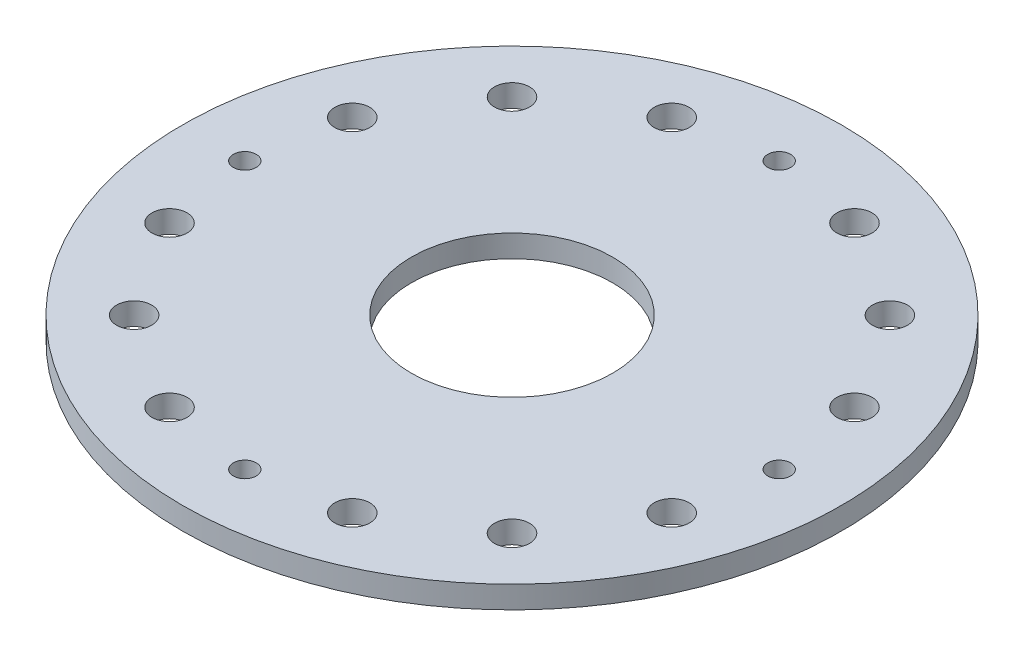
SolidWorks part; units mm, degrees
ref_plane "Front Plane" through (0, 0, 0) normal (0, 0, 1) x (1, 0, 0)
ref_plane "Top Plane" through (0, 0, 0) normal (0, 1, 0) x (1, 0, 0)
ref_plane "Right Plane" through (0, 0, 0) normal (1, 0, 0) x (0, 0, -1)
sketch "Sketch1" plane through (0, 0, 0) normal (0, 1, 0) x (1, 0, 0)
  circle A0 centre (0, 0) radius 46.99
  dimension "D1" = 93.98
extrude "Boss-Extrude1" add sketch "Sketch1" along normal blind 3.175
sketch "Sketch2" plane through (0, 3.175, 0) normal (0, 1, 0) x (1, 0, 0)
  circle A0 centre (0, 0) radius 14.351
  dimension "D1" = 28.702
extrude "Cut-Extrude1" cut sketch "Sketch2" against normal blind 3.175
hole_wizard "#4 Clearance Hole1" positions "Sketch4" profile "Sketch3" hole size "#4" standard "ANSI Inch"
sketch "Sketch4" plane through (0, 3.175, 0) normal (0, 1, 0) x (1, 0, 0)
  point P0 (0, 38.1)
  dimension "D1" = 38.1
sketch "Sketch3" plane through (0, 3.175, -38.1) normal (1, 0, 0) x (0, 0, 1)
  line L0 (0, 0) -> (0, 11.1406)
  line L1 (0, 11.1406) -> (1.6319, 10.16)
  line L2 (1.6319, 10.16) -> (1.6319, 0)
  line L5 (1.6319, 0) -> (0, 0)
  line L10 (0, 11.1406) -> (-1.632, 10.16) construction
  line L11 (0, -6.35) -> (0, 107.95) construction
  dimension "Hole Dia." = 3.2639
  dimension "Hole Depth" = 10.16
  dimension "Drill Angle" = 118
pattern_circular "CirPattern1" count 4 every 90 about axis through (0, 0, 0) along (0, 1, 0) of "#4 Clearance Hole1"
sketch "Sketch5" plane through (0, 3.175, 0) normal (0, 1, 0) x (1, 0, 0)
  line L0 (0, 0) -> (-26.9408, 26.9408)
  line L1 (0, 38.1) -> (0, -38.1) construction
  circle A0 centre (-26.9408, 26.9408) radius 2.5
  dimension "D1" = 5
  dimension "D2" = 38.1
  dimension "D3" = 45
extrude "Cut-Extrude2" cut sketch "Sketch5" against normal blind 5.08
pattern_circular "CirPattern2" count 4 over 360 about axis through (0, 0, 0) along (0, 1, 0) of "Cut-Extrude2"
pattern_circular "CirPattern3" count 2 every 25 about axis through (0, 0, 0) along (0, 1, 0) of "CirPattern2", "Cut-Extrude2"
pattern_circular "CirPattern4" count 2 every 25 about axis through (0, 0, 0) along (0, 1, 0) of "CirPattern2", "Cut-Extrude2"
